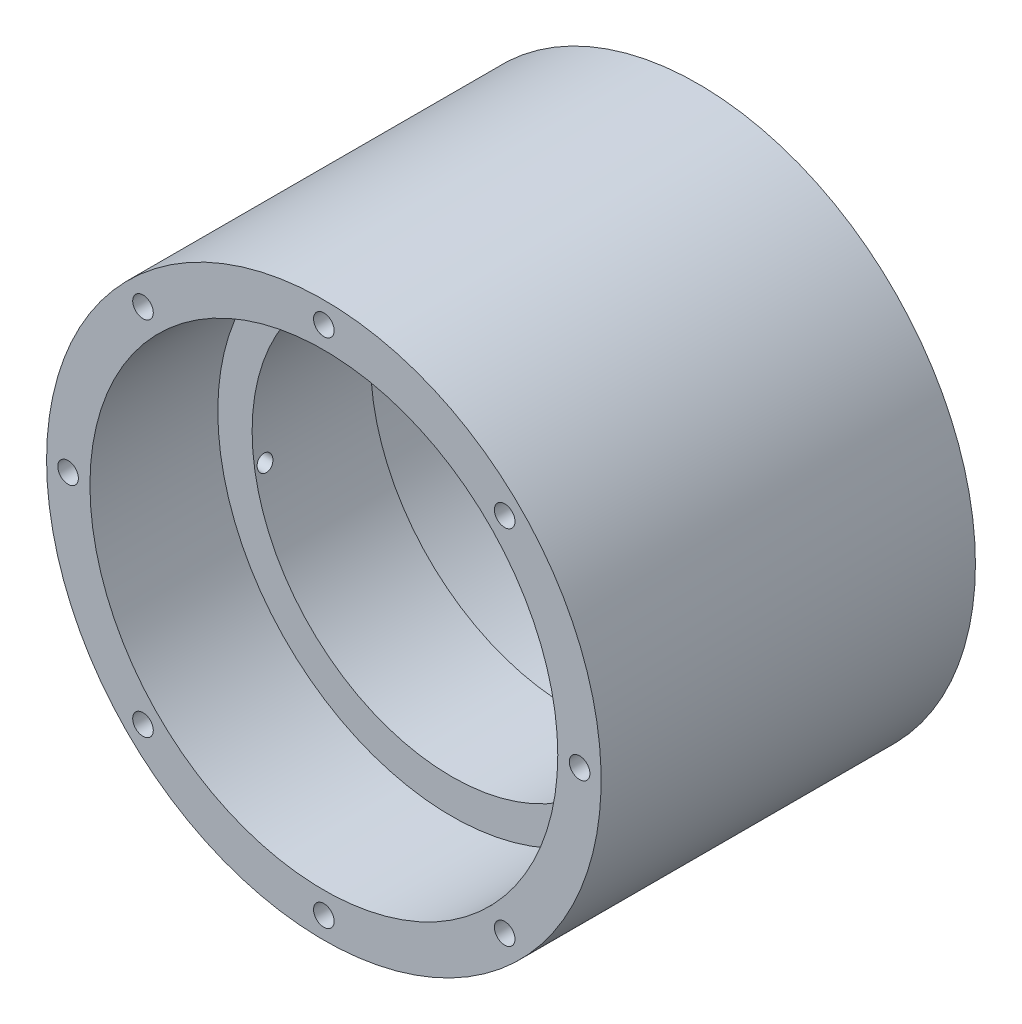
SolidWorks part; units mm, degrees
material "6061 Alloy"
ref_plane "Front" through (0, 0, 0) normal (0, 0, 1) x (1, 0, 0)
ref_plane "Top" through (0, 0, 0) normal (0, 1, 0) x (1, 0, 0)
ref_plane "Right" through (0, 0, 0) normal (1, 0, 0) x (0, 0, -1)
ref_plane "Plane1" through (0, 0, 0) normal (0, -1, 0) x (1, 0, 0)
sketch "Sketch1" plane through (0, 0, 0) normal (0, -1, 0) x (1, 0, 0)
  line L0 (44.45, 60) -> (0, 60)
  line L1 (0, 60) -> (0, 0)
  line L2 (0, 0) -> (44.45, 0)
  line L3 (44.45, 0) -> (44.45, 60)
  line L4 (0, 60) -> (0, 0) construction
revolve "Revolve1" add sketch "Sketch1" angle 360 about L4
sketch "Sketch2" plane through (0, 0, 0) normal (0, 0, -1) x (-1, 0, 0)
  line L0 (43.7242, 8) -> (43.7242, -8)
  arc A0 (43.7242, -8) -> (43.7242, 8) centre (0, 0) ccw
extrude "Cut-Extrude1" cut sketch "Sketch2" against normal blind 50
sketch "Sketch3" plane through (0, 0, 0) normal (0, -1, 0) x (1, 0, 0)
  line L0 (37.5, 60) -> (0, 60)
  line L1 (0, 60) -> (0, 0)
  line L2 (0, 0) -> (37.5, 0)
  line L3 (37.5, 0) -> (37.5, 20.5)
  line L4 (37.5, 20.5) -> (32, 20.5)
  line L5 (32, 20.5) -> (32, 39.5)
  line L6 (32, 39.5) -> (37.5, 39.5)
  line L7 (37.5, 39.5) -> (37.5, 60)
  line L8 (0, 60) -> (0, 0) construction
revolve "Cut-Revolve1" cut sketch "Sketch3" angle 360 about L8
hole_wizard "M4x0.7 Tapped Hole1" positions "Sketch5" profile "Sketch4" tap size "M4x0.7" standard "ANSI Metric"
sketch "Sketch5" plane through (0, 0, 60) normal (0, 0, 1) x (1, 0, 0)
  point P0 (28.9914, 28.9914)
  point P1 (0, 41)
  point P2 (-28.9914, 28.9914)
  point P3 (-41, 0)
  point P4 (-28.9914, -28.9914)
  point P5 (0, -41)
  point P6 (28.9914, -28.9914)
  point P7 (41, 0)
sketch "Sketch4" plane through (28.9914, 28.9914, 60) normal (1, 0, 0) x (0, -1, 0)
  line L0 (0, 0) -> (0, 10.9914)
  line L1 (0, 10.9914) -> (1.65, 10)
  line L2 (1.65, 10) -> (1.65, 0)
  line L5 (1.65, 0) -> (0, 0)
  line L10 (0, 10.9914) -> (-1.65, 10) construction
  line L11 (0, -6.35) -> (0, 107.95) construction
  dimension "Tap Drill Dia." = 3.3
  dimension "Tap Drill Depth" = 10
  dimension "Drill Angle" = 118
hole_wizard "M3x0.5 Tapped Hole1" positions "Sketch7" profile "Sketch6" tap size "M3x0.5" standard "ANSI Metric"
sketch "Sketch7" plane through (-43.7242, 0, 0) normal (-1, 0, 0) x (0, 0, 1)
  point P0 (15.5847, 5.15)
sketch "Sketch6" plane through (-43.7242, 5.15, 15.5847) normal (0, 1, 0) x (0, 0, 1)
  line L0 (0, 0) -> (0, 6.5795)
  line L1 (0, 6.5795) -> (1.25, 6.5795)
  line L2 (1.25, 6.5795) -> (1.25, 0)
  line L5 (1.25, 0) -> (0, 0)
  line L11 (0, -6.35) -> (0, 107.95) construction
  dimension "Thru Tap Drill Dia." = 2.5
  dimension "Thru Tap Drill Depth" = 6.5795
hole_wizard "M3x0.5 Tapped Hole2" positions "Sketch9" profile "Sketch8" tap size "M3x0.5" standard "ANSI Metric"
sketch "Sketch9" plane through (-43.7242, 0, 0) normal (-1, 0, 0) x (0, 0, 1)
  point P0 (37.8347, -5.05)
sketch "Sketch8" plane through (-43.7242, -5.05, 37.8347) normal (0, 1, 0) x (0, 0, 1)
  line L0 (0, 0) -> (0, 12.1252)
  line L1 (0, 12.1252) -> (1.25, 12.1252)
  line L2 (1.25, 12.1252) -> (1.25, 0)
  line L5 (1.25, 0) -> (0, 0)
  line L11 (0, -6.35) -> (0, 107.95) construction
  dimension "Thru Tap Drill Dia." = 2.5
  dimension "Thru Tap Drill Depth" = 12.1252
